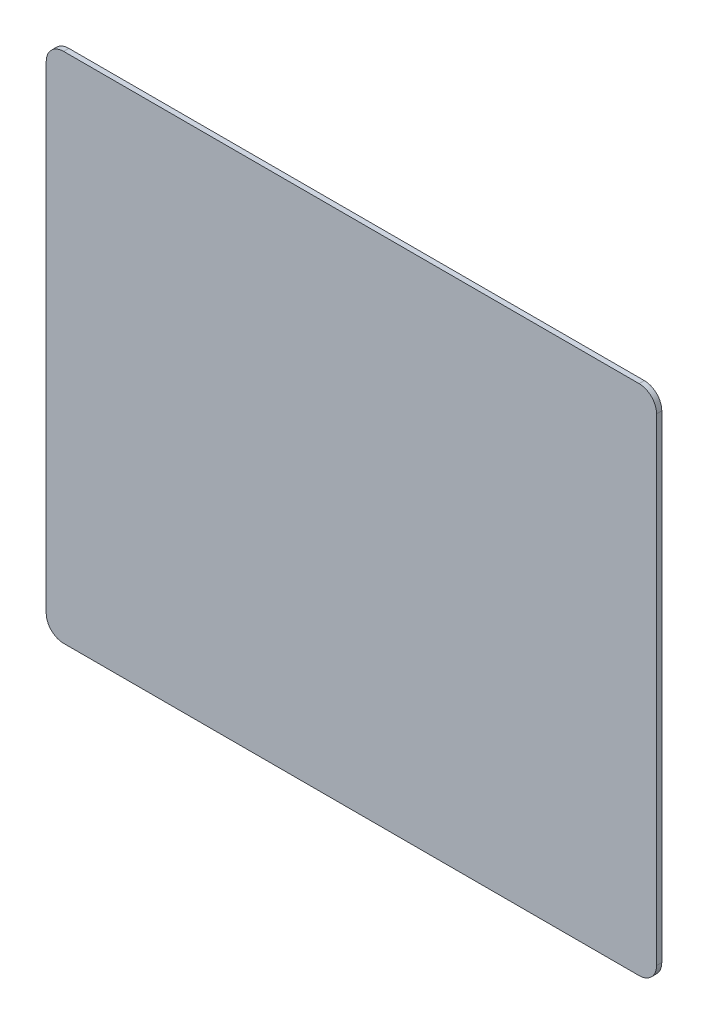
SolidWorks part; units mm, degrees
ref_plane "Front Plane" through (0, 0, 0) normal (0, 0, 1) x (1, 0, 0)
ref_plane "Top Plane" through (0, 0, 0) normal (0, 1, 0) x (1, 0, 0)
ref_plane "Right Plane" through (0, 0, 0) normal (1, 0, 0) x (0, 0, -1)
sketch "Sketch1" plane through (0, 0, 0) normal (0, 0, 1) x (1, 0, 0)
  line L1 (-350, -294) -> (350, -294)
  line L2 (-350, -294) -> (-350, 294)
  line L3 (-350, 294) -> (350, 294)
  line L4 (350, -294) -> (350, 294)
  line L5 (-350, -294) -> (350, 294) construction
  line L6 (-350, 294) -> (350, -294) construction
  point P0 (0, 0)
  dimension "D1" = 588
  dimension "D2" = 700
extrude "Boss-Extrude1" add sketch "Sketch1" along normal blind 6
fillet "Fillet1" radius 20 4 edges at (-350, 294, 3) (350, 294, 3) (350, -294, 3) (-350, -294, 3)
sketch "Sketch2" plane through (0, 0, 6) normal (0, 0, 1) x (1, 0, 0)
  line L0 (-350, 274) -> (-350, -274) construction
  line L1 (-188, -208) -> (228, -208)
  line L2 (-188, -208) -> (-188, 208)
  line L3 (-188, 208) -> (228, 208)
  line L4 (228, -208) -> (228, 208)
  line L5 (-188, -220) -> (228, -220) construction
  line L13 (-188, 104) -> (-136, 104)
  line L14 (-188, 208) -> (-136, 208)
  line L15 (-188, 208) -> (-188, 156)
  line L16 (-188, 156) -> (-136, 156)
  line L17 (-136, 208) -> (-136, 156)
  line L18 (-136, 156) -> (-136, 104)
  line L19 (-188, 52) -> (-136, 52)
  line L20 (-136, 104) -> (-136, 52)
  line L21 (-188, 0) -> (-136, 0)
  line L22 (-136, 52) -> (-136, 0)
  line L23 (-188, -52) -> (-136, -52)
  line L24 (-136, 0) -> (-136, -52)
  line L25 (-188, -104) -> (-136, -104)
  line L26 (-136, -52) -> (-136, -104)
  line L27 (-188, -156) -> (-136, -156)
  line L28 (-136, -104) -> (-136, -156)
  line L29 (-188, -208) -> (-136, -208)
  line L30 (-136, -156) -> (-136, -208)
  line L31 (-136, 156) -> (-84, 156)
  line L32 (-84, 208) -> (-84, 156)
  line L33 (-136, 104) -> (-84, 104)
  line L34 (-84, 156) -> (-84, 104)
  line L35 (-136, 52) -> (-84, 52)
  line L36 (-84, 104) -> (-84, 52)
  line L37 (-136, 0) -> (-84, 0)
  line L38 (-84, 52) -> (-84, 0)
  line L39 (-136, -52) -> (-84, -52)
  line L40 (-84, 0) -> (-84, -52)
  line L41 (-136, -104) -> (-84, -104)
  line L42 (-84, -52) -> (-84, -104)
  line L43 (-136, -156) -> (-84, -156)
  line L44 (-84, -104) -> (-84, -156)
  line L45 (-84, -156) -> (-84, -208)
  line L46 (-84, 156) -> (-32, 156)
  line L47 (-32, 208) -> (-32, 156)
  line L48 (-84, 104) -> (-32, 104)
  line L49 (-32, 156) -> (-32, 104)
  line L50 (-84, 52) -> (-32, 52)
  line L51 (-32, 104) -> (-32, 52)
  line L52 (-84, 0) -> (-32, 0)
  line L53 (-32, 52) -> (-32, 0)
  line L54 (-84, -52) -> (-32, -52)
  line L55 (-32, 0) -> (-32, -52)
  line L56 (-84, -104) -> (-32, -104)
  line L57 (-32, -52) -> (-32, -104)
  line L58 (-84, -156) -> (-32, -156)
  line L59 (-32, -104) -> (-32, -156)
  line L60 (-32, -156) -> (-32, -208)
  line L61 (-32, 156) -> (20, 156)
  line L62 (20, 208) -> (20, 156)
  line L63 (-32, 104) -> (20, 104)
  line L64 (20, 156) -> (20, 104)
  line L65 (-32, 52) -> (20, 52)
  line L66 (20, 104) -> (20, 52)
  line L67 (-32, 0) -> (20, 0)
  line L68 (20, 52) -> (20, 0)
  line L69 (-32, -52) -> (20, -52)
  line L70 (20, 0) -> (20, -52)
  line L71 (-32, -104) -> (20, -104)
  line L72 (20, -52) -> (20, -104)
  line L73 (-32, -156) -> (20, -156)
  line L74 (20, -104) -> (20, -156)
  line L75 (20, -156) -> (20, -208)
  line L76 (20, 156) -> (72, 156)
  line L77 (72, 208) -> (72, 156)
  line L78 (20, 104) -> (72, 104)
  line L79 (72, 156) -> (72, 104)
  line L80 (20, 52) -> (72, 52)
  line L81 (72, 104) -> (72, 52)
  line L82 (20, 0) -> (72, 0)
  line L83 (72, 52) -> (72, 0)
  line L84 (20, -52) -> (72, -52)
  line L85 (72, 0) -> (72, -52)
  line L86 (20, -104) -> (72, -104)
  line L87 (72, -52) -> (72, -104)
  line L88 (20, -156) -> (72, -156)
  line L89 (72, -104) -> (72, -156)
  line L90 (72, -156) -> (72, -208)
  line L91 (72, 156) -> (124, 156)
  line L92 (124, 208) -> (124, 156)
  line L93 (72, 104) -> (124, 104)
  line L94 (124, 156) -> (124, 104)
  line L95 (72, 52) -> (124, 52)
  line L96 (124, 104) -> (124, 52)
  line L97 (72, 0) -> (124, 0)
  line L98 (124, 52) -> (124, 0)
  line L99 (72, -52) -> (124, -52)
  line L100 (124, 0) -> (124, -52)
  line L101 (72, -104) -> (124, -104)
  line L102 (124, -52) -> (124, -104)
  line L103 (72, -156) -> (124, -156)
  line L104 (124, -104) -> (124, -156)
  line L105 (124, -156) -> (124, -208)
  line L106 (124, 156) -> (176, 156)
  line L107 (176, 208) -> (176, 156)
  line L108 (124, 104) -> (176, 104)
  line L109 (176, 156) -> (176, 104)
  line L110 (124, 52) -> (176, 52)
  line L111 (176, 104) -> (176, 52)
  line L112 (124, 0) -> (176, 0)
  line L113 (176, 52) -> (176, 0)
  line L114 (124, -52) -> (176, -52)
  line L115 (176, 0) -> (176, -52)
  line L116 (124, -104) -> (176, -104)
  line L117 (176, -52) -> (176, -104)
  line L118 (124, -156) -> (176, -156)
  line L119 (176, -104) -> (176, -156)
  line L120 (176, -156) -> (176, -208)
  line L121 (176, 156) -> (228, 156)
  line L122 (228, 208) -> (228, 156)
  line L123 (176, 104) -> (228, 104)
  line L124 (228, 156) -> (228, 104)
  line L125 (176, 52) -> (228, 52)
  line L126 (228, 104) -> (228, 52)
  line L127 (176, 0) -> (228, 0)
  line L128 (228, 52) -> (228, 0)
  line L129 (176, -52) -> (228, -52)
  line L130 (228, 0) -> (228, -52)
  line L131 (176, -104) -> (228, -104)
  line L132 (228, -52) -> (228, -104)
  line L133 (176, -156) -> (228, -156)
  line L134 (228, -104) -> (228, -156)
  line L135 (228, -156) -> (228, -208)
  line L137 (-193, -208) -> (-193, 208) construction
  line L138 (330, 294) -> (-330, 294) construction
  line L139 (-330, -294) -> (330, -294) construction
  line L144 (-315, -279) -> (-243.7, -279)
  line L151 (-315, -279) -> (-315, -254.6)
  line L152 (-315, -254.6) -> (-243.7, -254.6)
  line L153 (-243.7, -279) -> (-243.7, -254.6)
  line L154 (-262, -225) -> (302, -225)
  line L155 (-272, -215) -> (-272, 215)
  line L156 (-262, 225) -> (302, 225)
  line L157 (312, -215) -> (312, 215)
  line L158 (-272, -225) -> (312, 225) construction
  line L159 (-272, 225) -> (312, -225) construction
  line L163 (188.4646, -283.6) -> (311, -283.6)
  line L168 (-320.35, -283.6) -> (-238.35, -283.6)
  line L169 (-320.35, -283.6) -> (-320.35, -249.6)
  line L170 (-320.35, -249.6) -> (-238.35, -249.6)
  line L171 (-238.35, -283.6) -> (-238.35, -249.6)
  line L172 (-320.35, -283.6) -> (-238.35, -249.6) construction
  line L173 (-320.35, -249.6) -> (-238.35, -283.6) construction
  circle A41 centre (-252, -155.5) radius 13
  circle A42 centre (-220, -178) radius 15
  circle A43 centre (-220, -133) radius 15
  circle A44 centre (-220, -88) radius 15
  circle A45 centre (-220, -43) radius 15
  circle A46 centre (-220, 2) radius 15
  circle A47 centre (-220, 47) radius 15
  circle A48 centre (-220, 92) radius 15
  circle A49 centre (-220, 137) radius 15
  circle A50 centre (-220, 182) radius 15
  circle A51 centre (-252, -110.5) radius 13
  circle A52 centre (-252, -65.5) radius 13
  circle A53 centre (-252, -20.5) radius 13
  circle A54 centre (-252, 24.5) radius 13
  circle A55 centre (-252, 69.5) radius 13
  circle A56 centre (-252, 114.5) radius 13
  circle A57 centre (-252, 159.5) radius 13
  circle A58 centre (260, -178) radius 15
  circle A59 centre (292, 159.5) radius 13
  circle A60 centre (292, 114.5) radius 13
  circle A61 centre (292, 69.5) radius 13
  circle A62 centre (292, 24.5) radius 13
  circle A63 centre (292, -20.5) radius 13
  circle A64 centre (292, -65.5) radius 13
  circle A65 centre (292, -110.5) radius 13
  circle A66 centre (260, 182) radius 15
  circle A67 centre (260, 137) radius 15
  circle A68 centre (260, 92) radius 15
  circle A69 centre (260, 47) radius 15
  circle A70 centre (260, 2) radius 15
  circle A71 centre (260, -43) radius 15
  circle A72 centre (260, -88) radius 15
  circle A73 centre (260, -133) radius 15
  circle A74 centre (292, -155.5) radius 13
  arc A75 (302, 225) -> (312, 215) centre (302, 215) cw
  arc A76 (-272, 215) -> (-262, 225) centre (-262, 215) cw
  arc A77 (302, -225) -> (312, -215) centre (302, -215) ccw
  arc A78 (-262, -225) -> (-272, -215) centre (-262, -215) cw
  circle A79 centre (-315, -225) radius 14.4
  text T0 "A B C D E F G H" font "Calibri" height in points 26
  text T1 "1 2 3 4 5 6 7 8" font "Calibri" height in points 26
  text T2 "Masteroppgave Emil Aasen Skogheim" font "Century Gothic" height in points 16
  point P226 (-279.35, -266.6)
  dimension "D4" = 30
  dimension "D8" = 45
  dimension "D16" = 32
  dimension "D17" = 450
  dimension "D21" = 416
  dimension "D26" = 71.3
  dimension "D29" = 10
  dimension "D6" = 26
  dimension "D27" = 15
  dimension "D28" = 12
  dimension "D31" = 35.65
  dimension "D30" = 28.8
  dimension "D1" = 416
  dimension "D2" = 162
  dimension "D3" = 208
  dimension "D5" = 22.5
  dimension "D7" = 30
  dimension "D9" = 52
  dimension "D10" = 8
  dimension "D12" = 45
  dimension "D13" = 8
  dimension "D15" = 32
  dimension "D18" = 584
  dimension "D20" = 24.4
  dimension "D22" = 12
  dimension "D23" = 416
  dimension "D24" = 0
  dimension "D25" = 5
  dimension "D14" = 9
  dimension "D32" = 35
  dimension "D33" = 82
  dimension "D34" = 34
  dimension "D11" = 8
